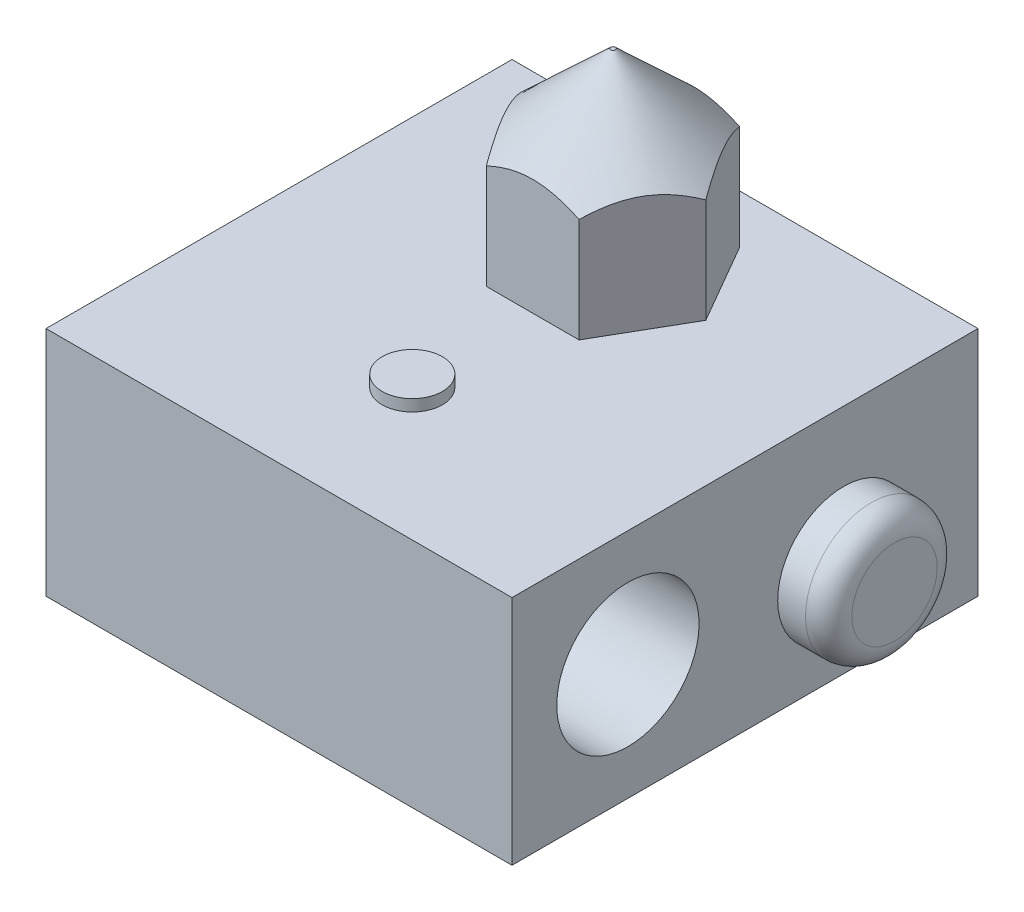
SolidWorks part; units mm, degrees
ref_plane "Front Plane" through (0, 0, 0) normal (0, 0, 1) x (1, 0, 0)
ref_plane "Top Plane" through (0, 0, 0) normal (0, 1, 0) x (1, 0, 0)
ref_plane "Right Plane" through (0, 0, 0) normal (1, 0, 0) x (0, 0, -1)
sketch "Sketch1" plane through (0, 0, 0) normal (0, 1, 0) x (1, 0, 0)
  line L1 (0, 0) -> (-20.1, 0)
  line L2 (0, 0) -> (0, 20.1)
  line L3 (0, 20.1) -> (-20.1, 20.1)
  line L4 (-20.1, 0) -> (-20.1, 20.1)
  dimension "D1" = 20.1
  dimension "D2" = 20.1
extrude "Boss-Extrude1" add sketch "Sketch1" along normal blind 10
sketch "Sketch2" plane through (0, 10, 0) normal (0, 1, 0) x (1, 0, 0)
  line L0 (0, 20.1) -> (-20.1, 20.1) construction
  line L1 (-8.1778, 18) -> (-12.1788, 18)
  line L2 (-12.1788, 18) -> (-14.1793, 14.535)
  line L3 (-14.1793, 14.535) -> (-12.1788, 11.07)
  line L4 (-12.1788, 11.07) -> (-8.1778, 11.07)
  line L5 (-8.1778, 11.07) -> (-6.1772, 14.535)
  line L6 (-6.1772, 14.535) -> (-8.1778, 18)
  circle A0 centre (-10.1783, 14.535) radius 3.465 construction
  point P1 (-10.1783, 18)
  point P11 (-7.9191, 17.9192)
  dimension "D1" = 6.93
  dimension "D2" = 2.1
extrude "Boss-Extrude2" add sketch "Sketch2" along normal blind 8.15
ref_plane "Plane1" through (0, 0, -14.535) normal (0, 0, -1) x (-1, 0, 0)
sketch "Sketch3" plane through (0, 0, -14.535) normal (0, 0, -1) x (-1, 0, 0)
  line L0 (10.2783, 18.15) -> (14.1793, 14.5)
  line L2 (14.1793, 18.15) -> (14.1793, 10) construction
  line L3 (14.1793, 14.5) -> (16.2019, 12.6076)
  line L4 (16.2019, 12.6076) -> (16.2019, 19.4653)
  line L5 (16.2019, 19.4653) -> (10.2783, 19.4653)
  line L7 (8.1778, 18.15) -> (12.1788, 18.15) construction
  line L8 (10.2783, 19.4653) -> (10.2783, 18.15)
  line L9 (10.1783, 18.15) -> (10.1783, 20.5457) construction
  point P2 (10.1783, 18.15)
  dimension "D1" = 4.5
  dimension "D2" = 0.1
revolve "Cut-Revolve1" cut sketch "Sketch3" angle 360 about L9
sketch "Sketch4" plane through (0, 0, 0) normal (1, 0, 0) x (0, 0, -1)
  line L0 (0, 10) -> (20.1, 10) construction
  line L1 (0, 10) -> (0, 0) construction
  circle A0 centre (5, 5) radius 3.07
  dimension "D1" = 6.14
  dimension "D2" = 5
  dimension "D3" = 5
extrude "Cut-Extrude1" cut sketch "Sketch4" against normal through all
sketch "Sketch5" plane through (0, 0, 0) normal (-1, 0, 0) x (0, 0, 1)
  line L0 (-20.1, 10) -> (0, 10) construction
  line L1 (-20.1, 10) -> (-20.1, 0) construction
  circle A0 centre (-14.3, 4.16) radius 2.84
  dimension "D1" = 5.68
  dimension "D2" = 5.84
  dimension "D3" = 5.8
extrude "Boss-Extrude3" add sketch "Sketch5" against normal blind 2.2
fillet "Fillet1" radius 1 1 edges at (2.2, 4.16, -11.46)
sketch "Sketch6" plane through (0, 0, 0) normal (0, -1, 0) x (1, 0, 0)
  line L0 (-4.4011, -14.535) -> (4.4011, -14.535) construction
  circle A0 centre (-10.1783, -14.535) radius 2.675
  circle A1 centre (-10.1783, -14.535) radius 0.1 construction
  dimension "D1" = 5.35
extrude "Cut-Extrude2" cut sketch "Sketch6" against normal blind 5.15
sketch "Sketch7" plane through (0, 10, 0) normal (0, 1, 0) x (1, 0, 0)
  line L0 (0, 0) -> (0, 20.1) construction
  line L1 (-20.1, 0) -> (0, 0) construction
  circle A0 centre (-10, 5.7) radius 1.3
  dimension "D1" = 2.6
  dimension "D2" = 10
  dimension "D3" = 5.7
extrude "Boss-Extrude4" add sketch "Sketch7" along normal blind 0.5
